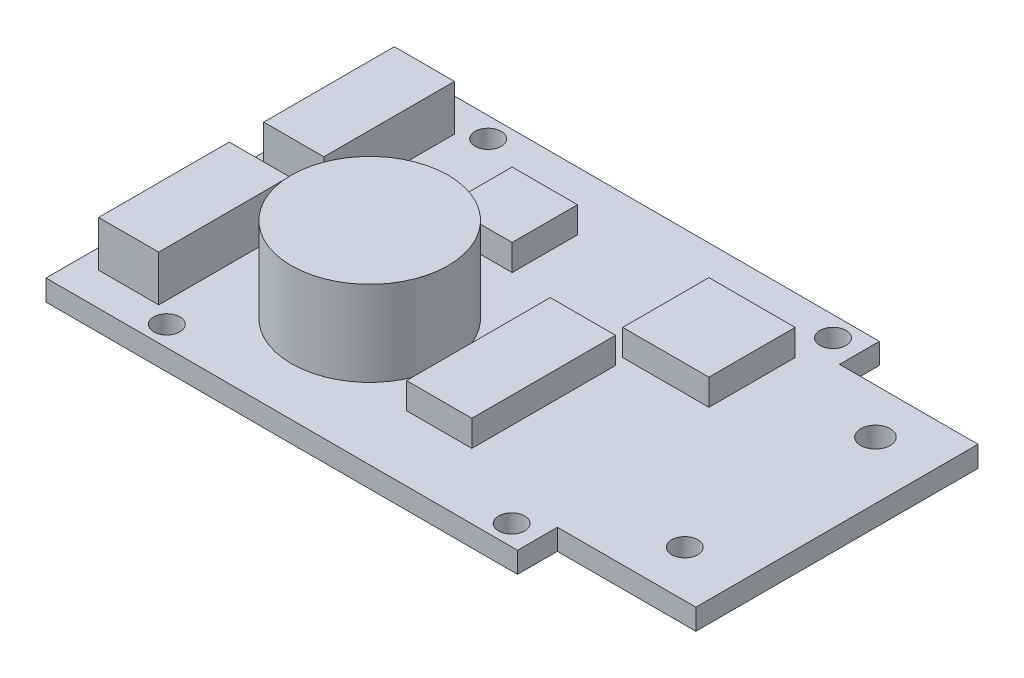
SolidWorks part; units mm, degrees
ref_plane "Alzado" through (0, 0, 0) normal (0, 0, 1) x (1, 0, 0)
ref_plane "Planta" through (0, 0, 0) normal (0, 1, 0) x (1, 0, 0)
ref_plane "Vista lateral" through (0, 0, 0) normal (1, 0, 0) x (0, 0, -1)
sketch "Croquis1" plane through (0, 0, 0) normal (0, 1, 0) x (1, 0, 0)
  line L1 (-18.05, 13.85) -> (18.05, 13.85)
  line L2 (-18.05, 13.85) -> (-18.05, -13.85)
  line L3 (-18.05, -13.85) -> (18.05, -13.85)
  line L4 (18.05, 13.85) -> (18.05, 10.8)
  line L5 (-18.05, 0) -> (34.2829, 0) construction
  line L7 (18.05, 10.8) -> (28.65, 10.8)
  line L9 (18.05, -10.8) -> (28.65, -10.8)
  line L10 (28.65, 10.8) -> (28.65, -10.8)
  line L11 (18.05, -10.8) -> (18.05, -13.85)
  circle A1 centre (-10.35, -12.3) radius 1
  circle A3 centre (16.05, -12.3) radius 1
  circle A5 centre (16.05, 12.3) radius 1
  circle A6 centre (-10.35, 12.3) radius 1
  point P0 (0, 0)
  dimension "D6" = 2
  dimension "D5" = 2
  dimension "D11" = 2
  dimension "D12" = 2
  dimension "D1" = 36.1
  dimension "D2" = 27.7
  dimension "D3" = 10.6
  dimension "D4" = 21.6
  dimension "D8" = 2
  dimension "D10" = 26.4
  dimension "D13" = 24.6
extrude "Saliente-Extruir1" add sketch "Croquis1" along normal blind 1.6
sketch "Croquis2" plane through (0, 1.6, 0) normal (0, 1, 0) x (1, 0, 0)
  line L0 (28.65, -10.8) -> (28.65, 10.8) construction
  line L3 (28.65, 0) -> (21.8887, 0) construction
  line L5 (18.05, -10.8) -> (28.65, -10.8) construction
  line L6 (28.65, 10.8) -> (18.05, 10.8) construction
  circle A0 centre (24.25, 7.25) radius 1
  circle A1 centre (24.25, -7.25) radius 1
  point P8 (0, 0)
  point P9 (0, 0)
  dimension "D1" = 2
  dimension "D2" = 2
  dimension "D3" = 4.4
  dimension "D4" = 4.4
  dimension "D5" = 3.55
  dimension "D6" = 3.55
extrude "Cortar-Extruir1" cut sketch "Croquis2" against normal blind 10
sketch "Croquis3" plane through (0, 1.6, 0) normal (0, 1, 0) x (1, 0, 0)
  line L0 (18.05, 10.8) -> (18.05, 13.85) construction
  line L1 (-16.55, 11.32) -> (-11.95, 11.32)
  line L2 (-16.55, 11.32) -> (-16.55, 1.32)
  line L3 (-16.55, 1.32) -> (-11.95, 1.32)
  line L4 (-11.95, 11.32) -> (-11.95, 1.32)
  line L5 (-16.55, -1.32) -> (-11.95, -1.32)
  line L6 (-16.55, -1.32) -> (-16.55, -11.32)
  line L7 (-16.55, -11.32) -> (-11.95, -11.32)
  line L8 (-11.95, -1.32) -> (-11.95, -11.32)
  line L9 (9.3, 9.55) -> (15.9, 9.55)
  line L10 (9.3, 9.55) -> (9.3, 2.95)
  line L11 (9.3, 2.95) -> (15.9, 2.95)
  line L12 (15.9, 9.55) -> (15.9, 2.95)
  line L13 (4.55, 2.15) -> (9.55, 2.15)
  line L14 (4.55, 2.15) -> (4.55, -8.85)
  line L15 (4.55, -8.85) -> (9.55, -8.85)
  line L16 (9.55, 2.15) -> (9.55, -8.85)
  line L17 (-5.564, 9.35) -> (-0.564, 9.35)
  line L18 (-5.564, 9.35) -> (-5.564, 4.35)
  line L19 (-5.564, 4.35) -> (-0.564, 4.35)
  line L20 (-0.564, 9.35) -> (-0.564, 4.35)
  line L21 (18.05, 13.85) -> (-18.05, 13.85) construction
  line L22 (-18.05, -13.85) -> (18.05, -13.85) construction
  line L23 (-18.05, 13.85) -> (-18.05, -13.85) construction
  line L24 (18.05, -13.85) -> (18.05, -10.8) construction
  circle A0 centre (-2.9796, -4.1398) radius 6
  dimension "D1" = 12
  dimension "D2" = 6.6
  dimension "D3" = 6.6
  dimension "D4" = 2.15
  dimension "D5" = 4.3
  dimension "D6" = 2.53
  dimension "D7" = 2.53
  dimension "D8" = 10
  dimension "D9" = 10
  dimension "D10" = 4.6
  dimension "D11" = 5
  dimension "D12" = 5
  dimension "D13" = 4.5
  dimension "D14" = 1.5
  dimension "D15" = 1.5
  dimension "D16" = 4.6
  dimension "D17" = 11
  dimension "D18" = 5
  dimension "D19" = 8.5
  dimension "D20" = 5
extrude "Saliente-Extruir2" add sketch "Croquis3" along normal blind 2
sketch "Croquis4" plane through (0, 3.6, 0) normal (0, 1, 0) x (1, 0, 0)
  circle A1 centre (-2.9796, -4.1398) radius 6
  circle A2 centre (-2.9796, -4.1398) radius 6
  dimension "D1" = 0
extrude "Saliente-Extruir3" add sketch "Croquis4" along normal blind 4.5
sketch "Croquis5" plane through (0, 3.6, 0) normal (0, 1, 0) x (1, 0, 0)
  line L4 (-16.55, 11.32) -> (-16.55, 1.32)
  line L5 (-16.55, 1.32) -> (-11.95, 1.32)
  line L6 (-11.95, 1.32) -> (-11.95, 11.32)
  line L7 (-11.95, 11.32) -> (-16.55, 11.32)
  line L8 (-16.55, 11.32) -> (-16.55, 1.32)
  line L9 (-16.55, 1.32) -> (-11.95, 1.32)
  line L10 (-11.95, 1.32) -> (-11.95, 11.32)
  line L11 (-11.95, 11.32) -> (-16.55, 11.32)
  line L12 (-16.55, -1.32) -> (-16.55, -11.32)
  line L13 (-16.55, -11.32) -> (-11.95, -11.32)
  line L14 (-11.95, -11.32) -> (-11.95, -1.32)
  line L15 (-11.95, -1.32) -> (-16.55, -1.32)
  line L16 (-16.55, -1.32) -> (-16.55, -11.32)
  line L17 (-16.55, -11.32) -> (-11.95, -11.32)
  line L18 (-11.95, -11.32) -> (-11.95, -1.32)
  line L19 (-11.95, -1.32) -> (-16.55, -1.32)
  dimension "D1" = 0
  dimension "D2" = 0
extrude "Saliente-Extruir4" add sketch "Croquis5" along normal blind 1.5
sketch "Croquis7" plane through (0, 0, 0) normal (0, -1, 0) x (1, 0, 0)
  circle A0 centre (24.25, -7.25) radius 1.1221
extrude "Saliente-Extruir5" add sketch "Croquis7" against normal up to surface (1.6 mm away) up to face at (-3.064, 1.6, -6.85)
sketch "Croquis9" plane through (0, 1.6, 0) normal (0, 1, 0) x (1, 0, 0)
  circle A0 centre (24.25, 7.35) radius 1.125
extrude "Cortar-Extruir2" cut sketch "Croquis9" against normal through all
